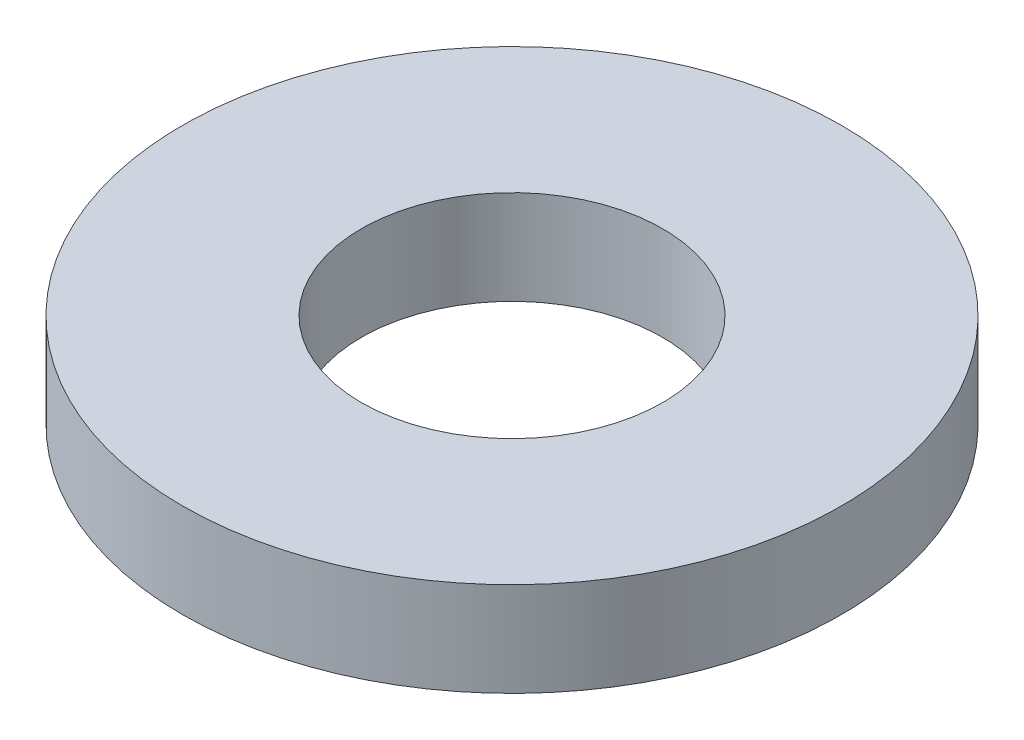
SolidWorks part; units mm, degrees
material "AISI 1045 Steel, cold drawn"
ref_plane "Front Plane" through (0, 0, 0) normal (0, 0, 1) x (1, 0, 0)
ref_plane "Top Plane" through (0, 0, 0) normal (0, 1, 0) x (1, 0, 0)
ref_plane "Right Plane" through (0, 0, 0) normal (1, 0, 0) x (0, 0, -1)
sketch "Sketch1" plane through (0, 0, 0) normal (0, 1, 0) x (1, 0, 0)
  circle A0 centre (0, 0) radius 1.6
  circle A1 centre (0, 0) radius 3.5
  dimension "D1" = 3.2
  dimension "D2" = 7
extrude "Boss-Extrude1" add sketch "Sketch1" along normal blind 1
